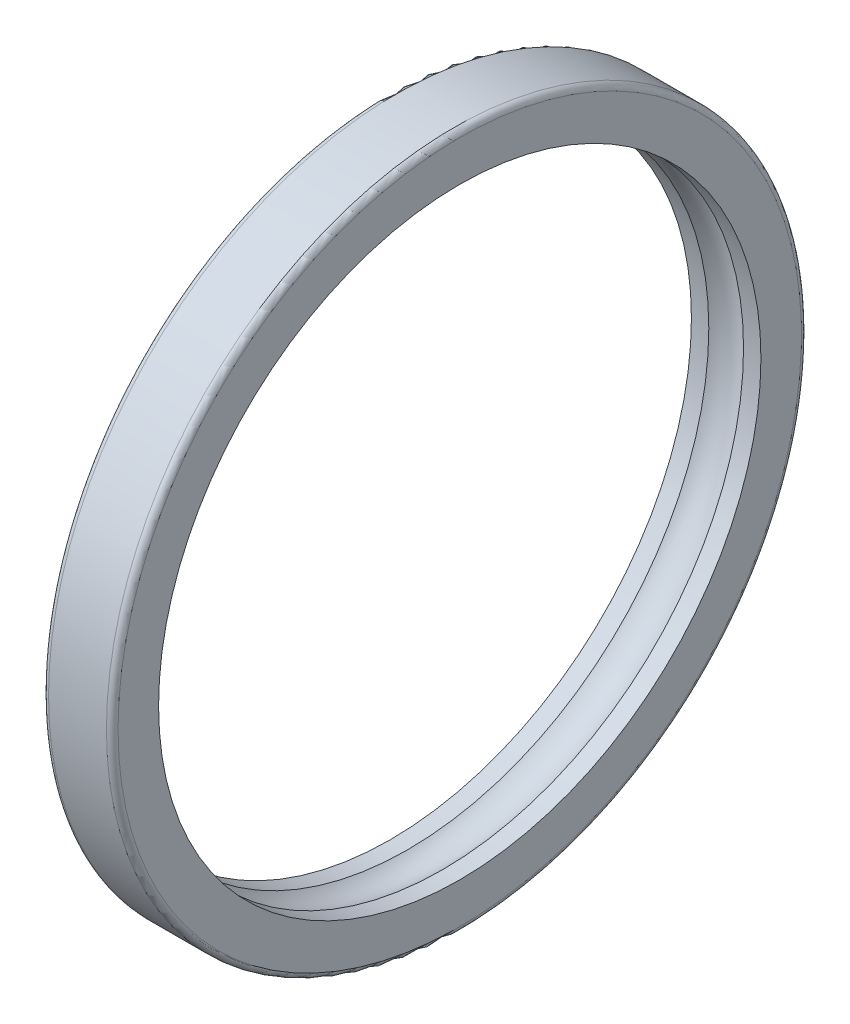
SolidWorks part; units mm, degrees
ref_plane "Front Plane" through (0, 0, 0) normal (0, 0, 1) x (1, 0, 0)
ref_plane "Top Plane" through (0, 0, 0) normal (0, 1, 0) x (1, 0, 0)
ref_plane "Right Plane" through (0, 0, 0) normal (1, 0, 0) x (0, 0, -1)
sketch "Sketch1" plane through (0, 0, 0) normal (0, 0, 1) x (1, 0, 0)
  line L0 (-3.81, 0) -> (4.5806, 0) construction
  line L1 (0, 35.56) -> (0, 0) construction
  line L2 (3.81, 38.1) -> (-3.81, 38.1)
  line L3 (3.81, 38.1) -> (3.81, 33.02)
  line L5 (-3.81, 38.1) -> (-3.81, 33.02)
  line L6 (3.81, 38.1) -> (-3.81, 33.02) construction
  line L7 (3.81, 33.02) -> (-3.81, 38.1) construction
  line L9 (-3.81, 33.02) -> (-1.905, 33.02)
  line L10 (1.905, 33.02) -> (3.81, 33.02)
  arc A1 (-1.905, 33.02) -> (1.905, 33.02) centre (0, 30.48) cw
  point P3 (0, 35.56)
  dimension "D4" = 3.175
  dimension "D5" = 7.62
  dimension "D1" = 7.62
  dimension "D2" = 5.08
  dimension "D3" = 33.02
revolve "Revolve2" add sketch "Sketch1" angle 360 about L0
fillet "Fillet1" radius 0.635 2 edges at (3.81, 0, 38.1) (-3.81, 0, 38.1)
